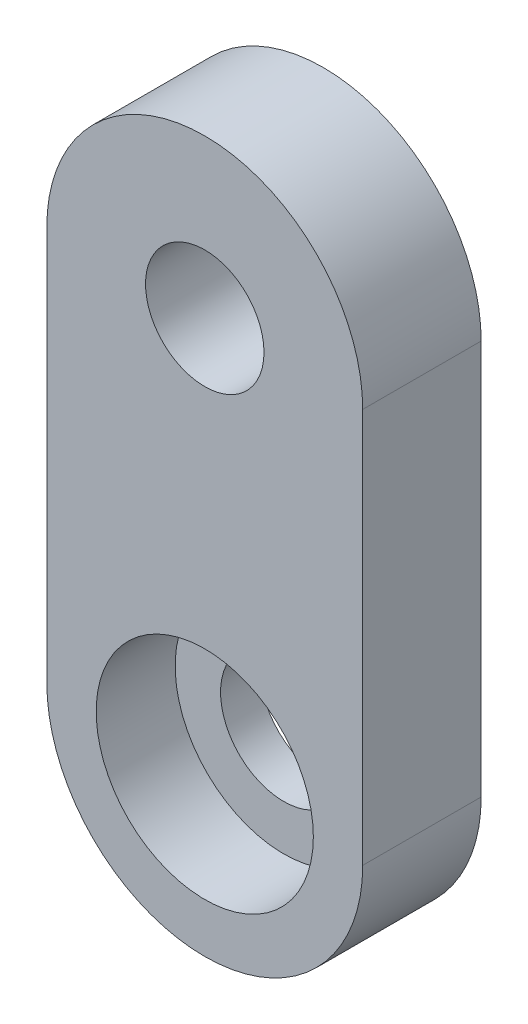
SolidWorks part; units mm, degrees
ref_plane "Front Plane" through (0, 0, 0) normal (1, 0, 0) x (0, 1, 0)
ref_plane "Top Plane" through (0, 0, 0) normal (0, 0, 1) x (0, 1, 0)
ref_plane "Right Plane" through (0, 0, 0) normal (0, 1, 0) x (-1, 0, 0)
sketch "Sketch2" plane through (0, 0, 0) normal (0, 0, 1) x (0, 1, 0)
  line L0 (0, 0) -> (12.7, 0) construction
  line L1 (0, 5.08) -> (12.7, 5.08)
  line L2 (0, -5.08) -> (12.7, -5.08)
  arc A2 (0, 5.08) -> (0, -5.08) centre (0, 0) ccw
  arc A3 (12.7, -5.08) -> (12.7, 5.08) centre (12.7, 0) ccw
  point P3 (6.35, 0)
  dimension "D1" = 10.16
  dimension "D2" = 12.7
extrude "base" add sketch "Sketch2" along normal blind 3.81
sketch "Sketch3" plane through (0, 0, 3.81) normal (0, 0, 1) x (1, 0, 0)
  circle A0 centre (0, 0) radius 2.032
  circle A1 centre (0, 12.7) radius 1.905
  dimension "D1" = 4.064
  dimension "D2" = 3.81
extrude "metric_holes" cut sketch "Sketch3" against normal up to next
sketch "Sketch4" plane through (0, 0, 3.81) normal (0, 0, 1) x (1, 0, 0)
  circle A0 centre (0, 0) radius 3.4925
  dimension "D1" = 6.985
extrude "Cut-Extrude2" cut sketch "Sketch4" against normal offset from surface (2.54 mm away) 1.27 up to face at (2.032, 0, 0)
